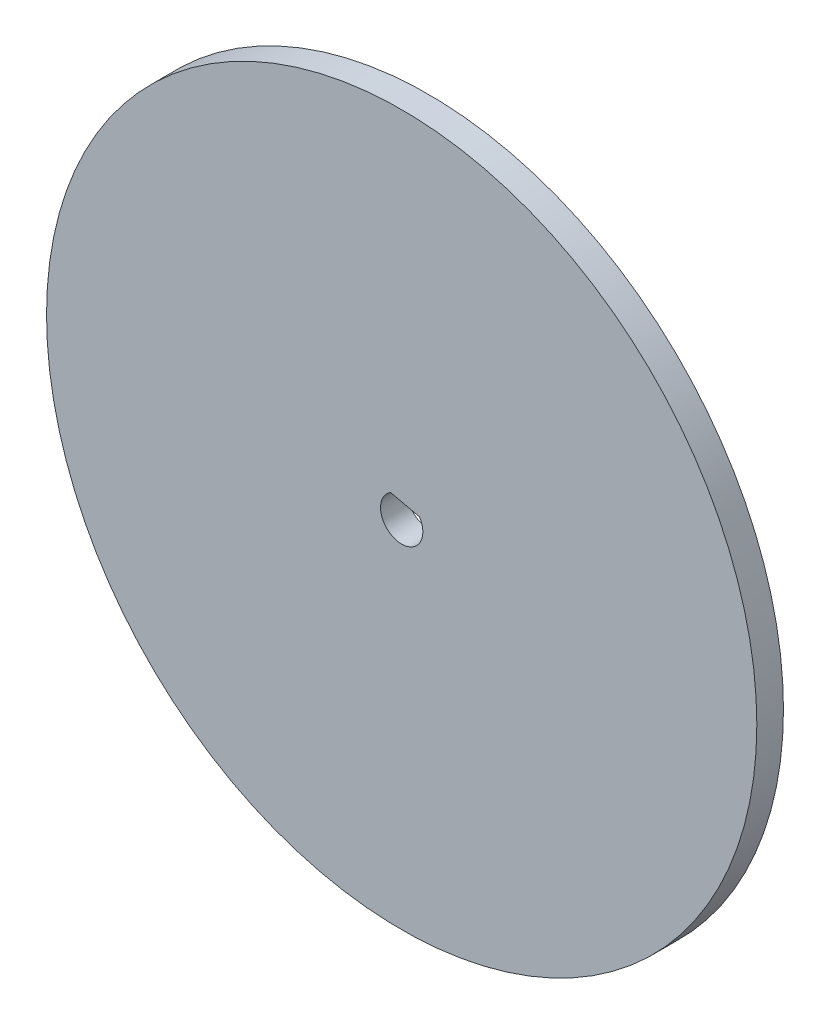
SolidWorks part; units mm, degrees
ref_plane "Front Plane" through (0, 0, 0) normal (0, 0, 1) x (1, 0, 0)
ref_plane "Top Plane" through (0, 0, 0) normal (0, 1, 0) x (1, 0, 0)
ref_plane "Right Plane" through (0, 0, 0) normal (1, 0, 0) x (0, 0, -1)
sketch "Sketch1" plane through (0, 0, 0) normal (0, 0, 1) x (1, 0, 0)
  circle A0 centre (0, 0) radius 40
  dimension "D1" = 80
extrude "Boss-Extrude1" add sketch "Sketch1" along normal blind 3
sketch "Sketch2" plane through (0, 0, 3) normal (0, 0, 1) x (1, 0, 0)
  line L0 (-1.2492, 2.0273) -> (2.0067, 1.282)
  arc A0 (-1.2492, 2.0273) -> (2.0067, 1.282) centre (0, 0) ccw
  dimension "D1" = 4.7625
  dimension "D2" = 2.0067
  dimension "D3" = 3.3401
extrude "Cut-Extrude1" cut sketch "Sketch2" against normal blind 3 contours A0 L0
equation "\"outer_diameter_spool\"= 80"
equation "\"D1@Sketch1\"=\"outer_diameter_spool\""
equation "\"depth\"=3"
equation "\"D1@Boss-Extrude1\"=\"depth\""
equation "\"laser_offset\"= 0.125"
equation "\"diameter_shaft\"=4.7625"
equation "\"D1@Sketch2\"=\"diameter_shaft\""
equation "\"D1@Cut-Extrude1\"= \"depth\""
